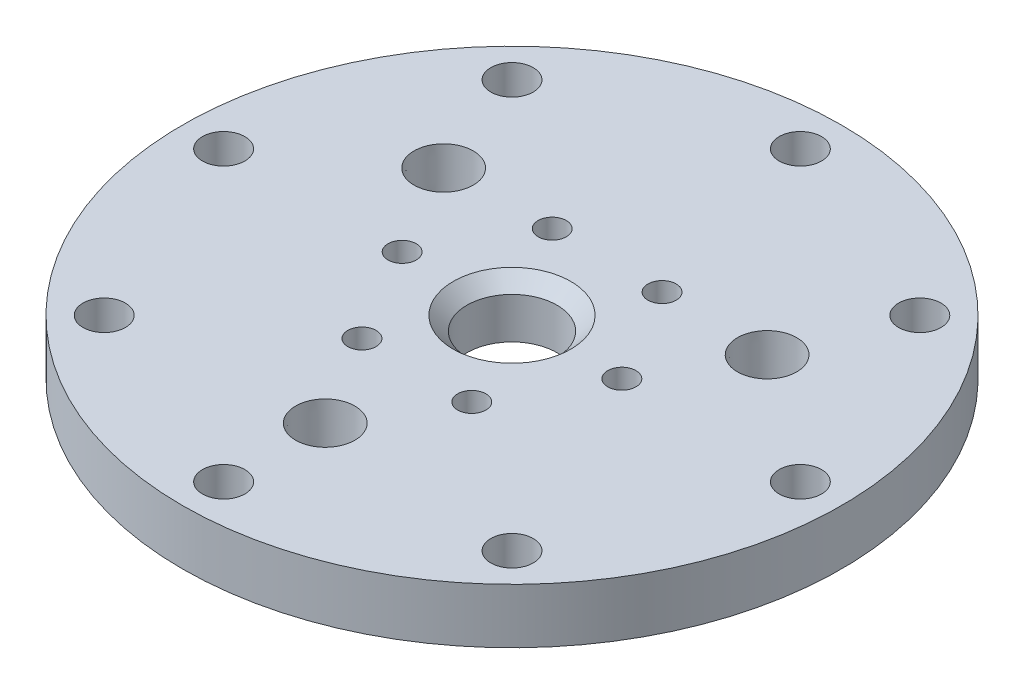
SolidWorks part; units mm, degrees
material "AISI Type 316L stainless steel"
ref_plane "Front Plane" through (0, 0, 0) normal (0, 0, 1) x (1, 0, 0)
ref_plane "Top Plane" through (0, 0, 0) normal (0, 1, 0) x (1, 0, 0)
ref_plane "Right Plane" through (0, 0, 0) normal (1, 0, 0) x (0, 0, -1)
sketch "Sketch1" plane through (0, 0, 0) normal (0, 1, 0) x (1, 0, 0)
  circle A0 centre (0, 0) radius 76.2
  dimension "D1" = 152.4
extrude "Boss-Extrude1" add sketch "Sketch1" along normal blind 12.7
hole_wizard "3/8 Clearance Hole1" positions "Sketch2" profile "Sketch3" hole size "3/8" standard "ANSI Inch" end condition through all
sketch "Sketch2" plane through (0, 12.7, 0) normal (0, 1, 0) x (1, 0, 0)
  line L1 (66.675, 0) -> (47.1463, 47.1463)
  line L2 (47.1463, 47.1463) -> (0, 66.675)
  line L3 (0, 66.675) -> (-47.1463, 47.1463)
  line L4 (-47.1463, 47.1463) -> (-66.675, 0)
  line L5 (-66.675, 0) -> (-47.1463, -47.1463)
  line L6 (-47.1463, -47.1463) -> (0, -66.675)
  line L7 (0, -66.675) -> (47.1463, -47.1463)
  line L8 (47.1463, -47.1463) -> (66.675, 0)
  line L9 (0, 0) -> (66.675, 0) construction
  circle A0 centre (0, 0) radius 66.675 construction
  point P3 (66.675, 0)
  point P4 (47.1463, 47.1463)
  point P5 (0, 66.675)
  point P6 (-47.1463, 47.1463)
  point P7 (-66.675, 0)
  point P8 (-47.1463, -47.1463)
  point P9 (0, -66.675)
  point P10 (47.1463, -47.1463)
  dimension "D1" = 133.35
sketch "Sketch3" plane through (47.1463, 12.7, 47.1463) normal (1, 0, 0) x (0, 0, 1)
  line L0 (0, 0) -> (0, 12.7)
  line L1 (0, 12.7) -> (4.9022, 12.7)
  line L2 (4.9022, 12.7) -> (4.9022, 0)
  line L5 (4.9022, 0) -> (0, 0)
  line L11 (0, -6.35) -> (0, 107.95) construction
  dimension "Thru Hole Dia." = 9.8044
  dimension "Thru Hole Depth" = 12.7
hole_wizard "1/4 Clearance Hole1" positions "Sketch4" profile "Sketch5" hole size "1/4" standard "ANSI Inch" end condition through all
sketch "Sketch4" plane through (0, 12.7, 0) normal (0, 1, 0) x (1, 0, 0)
  line L2 (25.4, 0) -> (12.7, 21.997)
  line L3 (12.7, 21.997) -> (-12.7, 21.997)
  line L4 (-12.7, 21.997) -> (-25.4, 0)
  line L5 (-25.4, 0) -> (-12.7, -21.997)
  line L6 (-12.7, -21.997) -> (12.7, -21.997)
  line L7 (12.7, -21.997) -> (25.4, 0)
  circle A0 centre (0, 0) radius 25.4 construction
  point P5 (25.4, 0)
  point P6 (12.7, 21.997)
  point P7 (-12.7, 21.997)
  point P8 (-25.4, 0)
  point P9 (-12.7, -21.997)
  point P10 (12.7, -21.997)
  dimension "D1" = 50.8
sketch "Sketch5" plane through (12.7, 12.7, 21.997) normal (1, 0, 0) x (0, 0, 1)
  line L0 (0, 0) -> (0, 12.7)
  line L1 (0, 12.7) -> (3.2639, 12.7)
  line L2 (3.2639, 12.7) -> (3.2639, 0)
  line L5 (3.2639, 0) -> (0, 0)
  line L11 (0, -6.35) -> (0, 107.95) construction
  dimension "Thru Hole Dia." = 6.5278
  dimension "Thru Hole Depth" = 12.7
hole_wizard "1/4 NPT Tapped Hole1" positions "Sketch6" profile "Sketch7" size "1/4" standard "ANSI Inch" end condition through all
sketch "Sketch6" plane through (0, 12.7, 0) normal (0, 1, 0) x (1, 0, 0)
  line L1 (0, -43.18) -> (37.395, 21.59)
  line L2 (37.395, 21.59) -> (-37.395, 21.59)
  line L3 (-37.395, 21.59) -> (0, -43.18)
  line L4 (0, 0) -> (0, -43.18) construction
  circle A0 centre (0, 0) radius 43.18 construction
  point P3 (0, -43.18)
  point P4 (37.395, 21.59)
  point P5 (-37.395, 21.59)
  dimension "D1" = 43.18
sketch "Sketch7" plane through (-37.395, 12.7, -21.59) normal (1, 0, 0) x (0, 0, 1)
  line L0 (0, 0) -> (0, 12.7)
  line L1 (0, 12.7) -> (5.5626, 12.7)
  line L2 (-6.558, 9.906) -> (-6.8546, 0) construction
  line L3 (5.5626, 12.7) -> (5.5626, 9.906)
  line L4 (5.5626, 9.906) -> (6.558, 9.906)
  line L5 (6.558, 9.906) -> (6.8546, 0)
  line L7 (6.8546, 0) -> (0, 0)
  line L8 (0, -6.35) -> (0, 107.95) construction
  line L11 (-5.5626, 9.906) -> (-6.558, 9.906) construction
  dimension "Thru Tap Drill Dia." = 11.1252
  dimension "Thru Tap Drill Depth" = 12.7
  dimension "Thread Dia." = 13.7092
  dimension "Thread Angle" = 3.43
  dimension "Thread Depth" = 9.906
sketch "Sketch8" plane through (0, 12.7, 0) normal (0, 1, 0) x (1, 0, 0)
  circle A0 centre (0, 0) radius 10.414
  dimension "D1" = 20.828
extrude "Cut-Extrude1" cut sketch "Sketch8" against normal through all
chamfer "Chamfer1" distance 3.175 angle 45 1 edges at (0, 12.7, 10.414)
